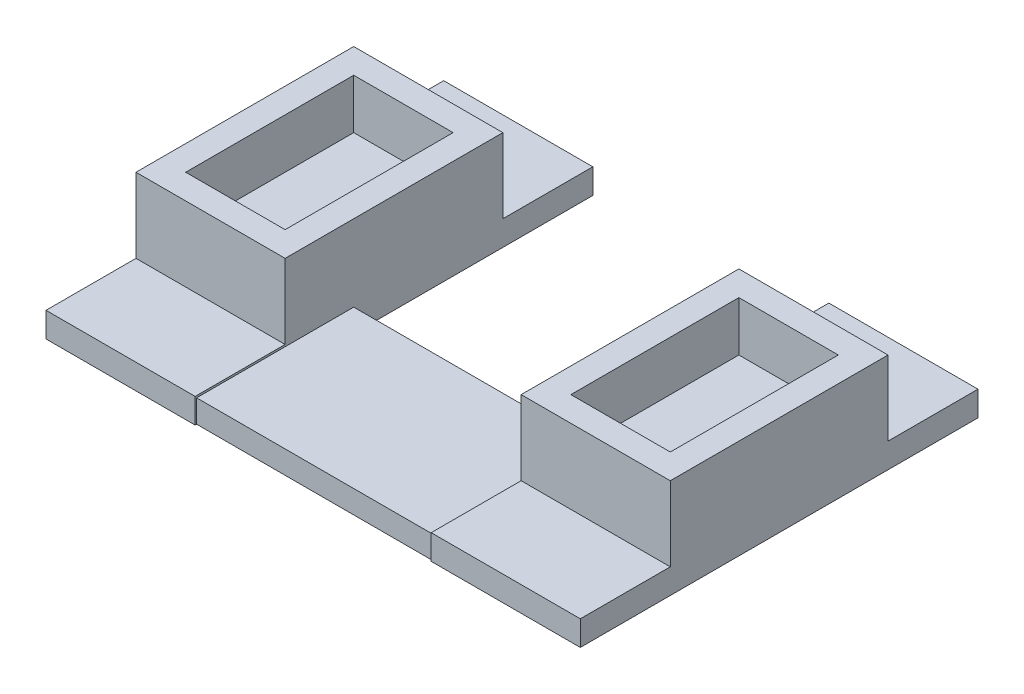
SolidWorks part; units mm, degrees
ref_plane "Front Plane" through (0, 0, 0) normal (0, 0, 1) x (1, 0, 0)
ref_plane "Top Plane" through (0, 0, 0) normal (0, 1, 0) x (1, 0, 0)
ref_plane "Right Plane" through (0, 0, 0) normal (1, 0, 0) x (0, 0, -1)
sketch "Sketch1" plane through (0, 0, 0) normal (0, 1, 0) x (1, 0, 0)
  line L0 (0, 50.6001) -> (0, 0) construction
  line L1 (0, 0) -> (59.7446, 0) construction
  line L6 (-30.9499, 10.7315) -> (-30.9499, -10.7315)
  line L7 (30.9499, 10.7315) -> (30.9499, -10.7315)
  line L8 (-30.9499, 50.6001) -> (-30.9499, 0) construction
  line L9 (30.9499, 50.6001) -> (30.9499, 0) construction
  line L10 (-34.1249, 13.9065) -> (-34.1249, -13.9065)
  line L11 (34.1249, 13.9065) -> (34.1249, -13.9065)
  line L12 (-30.9499, -10.7315) -> (-18.2499, -10.7315)
  line L13 (-30.9499, 10.7315) -> (-18.2499, 10.7315)
  line L14 (0, 10.7315) -> (59.7446, 10.7315) construction
  line L15 (0, -10.7315) -> (59.7446, -10.7315) construction
  line L16 (-34.1249, 13.9065) -> (-15.0749, 13.9065)
  line L17 (-34.1249, -13.9065) -> (-15.0749, -13.9065)
  line L18 (-30.9499, 13.9065) -> (34.1249, 13.9065) construction
  line L19 (-30.9499, 17.0699) -> (-30.9499, -17.0699) construction
  line L20 (-34.1249, 17.0699) -> (-34.1249, -17.0699) construction
  line L21 (-30.9499, 10.7315) -> (34.1249, 10.7315) construction
  line L22 (-18.2499, 10.7315) -> (-18.2499, -10.7315)
  line L23 (-15.0749, 13.9065) -> (-15.0749, -5.1435)
  line L24 (15.0749, 13.9065) -> (15.0749, -5.1435)
  line L25 (18.2499, 10.7315) -> (18.2499, -10.7315)
  line L28 (18.2499, -10.7315) -> (30.9499, -10.7315)
  line L29 (18.2499, 10.7315) -> (30.9499, 10.7315)
  line L30 (-15.0749, 10.7315) -> (-15.0749, -10.7315) construction
  line L31 (15.0749, 13.9065) -> (34.1249, 13.9065)
  line L32 (15.0749, -13.9065) -> (34.1249, -13.9065)
  line L33 (-15.0749, -13.9065) -> (15.0749, -13.9065)
  line L34 (-15.0749, -5.1435) -> (15.0749, -5.1435)
  dimension "D1" = 30.9499
  dimension "D2" = 30.9499
  dimension "D3" = 3.175
  dimension "D4" = 10.7315
  dimension "D5" = 10.7315
  dimension "D6" = 3.175
  dimension "D7" = 12.7
  dimension "D8" = 3.175
  dimension "D9" = 8.763
extrude "Boss-Extrude1" add sketch "Sketch1" along normal blind 6.35
sketch "Sketch2" plane through (0, 0, 0) normal (0, -1, 0) x (1, 0, 0)
  line L0 (-15.0749, 5.1435) -> (-15.0749, -13.9065)
  line L1 (-15.0749, -13.9065) -> (-34.1249, -13.9065)
  line L2 (-34.1249, -13.9065) -> (-34.1249, 13.9065)
  line L3 (-34.1249, -13.9065) -> (-34.1249, 13.9065) construction
  line L4 (-34.1249, 13.9065) -> (34.1249, 13.9065) construction
  line L5 (-34.1249, 13.9065) -> (34.1249, 13.9065)
  line L6 (34.1249, 13.9065) -> (34.1249, -13.9065)
  line L7 (34.1249, -13.9065) -> (15.0749, -13.9065) construction
  line L8 (34.1249, 13.9065) -> (34.1249, -13.9065) construction
  line L9 (34.1249, -13.9065) -> (15.0749, -13.9065)
  line L10 (15.0749, -13.9065) -> (15.0749, 5.1435)
  line L11 (15.0749, -13.9065) -> (15.0749, 5.1435) construction
  line L12 (15.0749, 5.1435) -> (-15.0749, 5.1435) construction
  line L13 (15.0749, 5.1435) -> (-15.0749, 5.1435)
extrude "Boss-Extrude2" add sketch "Sketch2" along normal blind 3.175
sketch "Sketch3" plane through (0, -3.175, 0) normal (0, -1, 0) x (1, 0, 0)
  line L0 (-34.1249, 0) -> (34.1249, 0) construction
  line L1 (-34.1249, 13.9065) -> (-34.1249, -13.9065) construction
  line L2 (34.1249, -13.9065) -> (34.1249, 13.9065) construction
  line L3 (-34.1249, -25.4) -> (-15.0749, -25.4)
  line L4 (-34.1249, 25.4) -> (-15.0749, 25.4)
  line L5 (-34.1249, 25.4) -> (-34.1249, -25.4)
  line L6 (34.1249, 25.4) -> (34.1249, -25.4)
  line L7 (15.0749, 25.4) -> (34.1249, 25.4)
  line L8 (-15.0749, -25.4) -> (-15.0749, 5.1435)
  line L9 (15.0749, -25.4) -> (15.0749, 5.1435)
  line L10 (-34.1249, 25.4) -> (34.1249, 25.4) construction
  line L11 (15.0749, -25.4) -> (34.1249, -25.4)
  line L12 (-34.1249, -25.4) -> (34.1249, -25.4) construction
  line L13 (15.0749, 13.9065) -> (-15.0749, 13.9065)
  line L14 (34.1249, 13.9065) -> (-34.1249, 13.9065) construction
  line L16 (-15.0749, 5.1435) -> (15.0749, 5.1435)
  line L18 (15.0749, 13.9065) -> (15.0749, 25.4)
  line L19 (-15.0749, 13.9065) -> (-15.0749, 25.4)
  dimension "D1" = 25.4
  dimension "D2" = 25.4
extrude "Boss-Extrude3" add sketch "Sketch3" along normal blind 3.175
sketch "Sketch4" plane through (0, 6.35, 0) normal (0, 1, 0) x (1, 0, 0)
  line L0 (-15.0749, -5.1435) -> (-15.0749, -13.9065)
  line L1 (-15.0749, -13.9065) -> (15.0749, -13.9065)
  line L2 (15.0749, -13.9065) -> (15.0749, -5.1435)
  line L3 (15.0749, -5.1435) -> (-15.0749, -5.1435)
extrude "Cut-Extrude1" cut sketch "Sketch4" against normal blind 9.779
sketch "Sketch6" plane through (0, 0, 13.9065) normal (0, 0, 1) x (1, 0, 0)
  line L0 (-15.0749, -3.429) -> (-15.0749, -6.35)
  line L1 (-15.0749, -6.35) -> (15.0749, -6.35)
  line L2 (15.0749, -6.35) -> (15.0749, -3.429)
  line L3 (15.0749, -3.429) -> (-15.0749, -3.429)
extrude "Boss-Extrude4" add sketch "Sketch6" along normal blind 11.303
